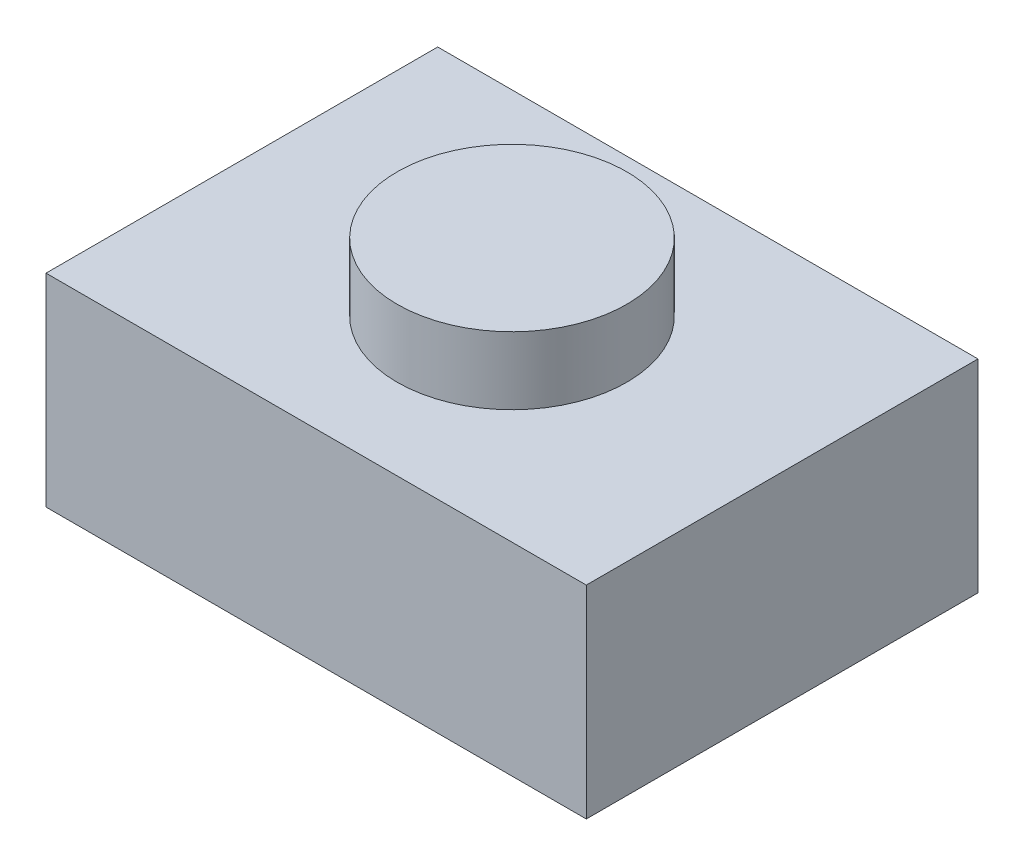
SolidWorks part; units mm, degrees
ref_plane "Alzado" through (0, 0, 0) normal (0, 0, 1) x (1, 0, 0)
ref_plane "Planta" through (0, 0, 0) normal (0, 1, 0) x (1, 0, 0)
ref_plane "Vista lateral" through (0, 0, 0) normal (1, 0, 0) x (0, 0, -1)
sketch "Croquis1" plane through (0, 0, 0) normal (0, 1, 0) x (1, 0, 0)
  line L1 (-2, -1.45) -> (2, -1.45)
  line L2 (-2, -1.45) -> (-2, 1.45)
  line L3 (-2, 1.45) -> (2, 1.45)
  line L4 (2, -1.45) -> (2, 1.45)
  line L5 (-2, -1.45) -> (2, 1.45) construction
  line L6 (-2, 1.45) -> (2, -1.45) construction
  point P0 (0, 0)
  dimension "D1" = 2.9
  dimension "D2" = 4
extrude "Saliente-Extruir1" add sketch "Croquis1" along normal blind 1.5
sketch "Croquis2" plane through (0, 1.5, 0) normal (0, 1, 0) x (1, 0, 0)
  circle A0 centre (0, 0) radius 0.85
  dimension "D1" = 1.7
extrude "Saliente-Extruir2" add sketch "Croquis2" along normal blind 0.5
